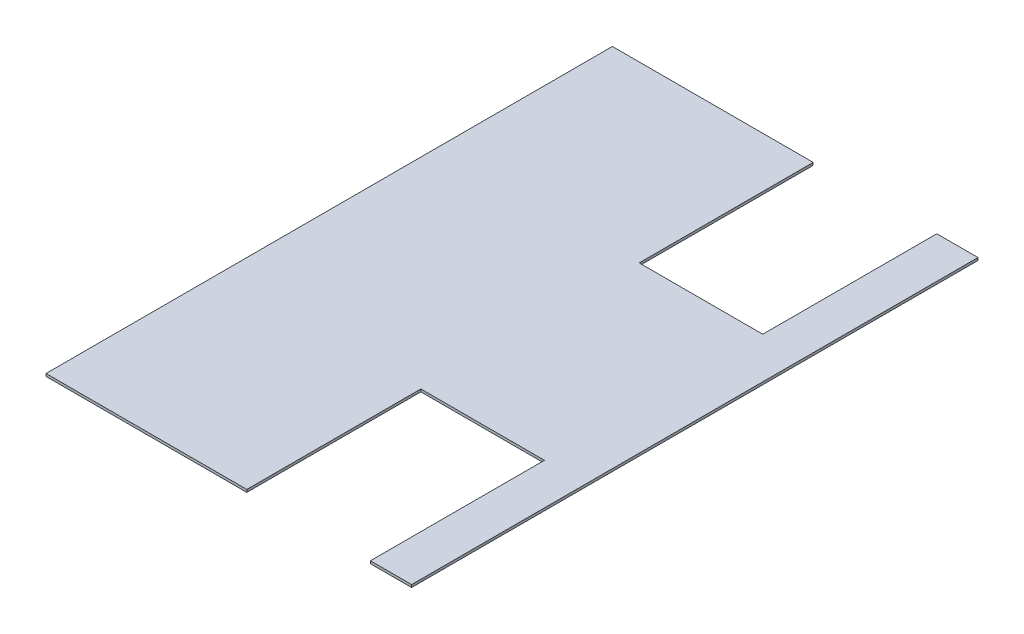
SolidWorks part; units mm, degrees
ref_plane "Front Plane" through (0, 0, 0) normal (0, 0, 1) x (1, 0, 0)
ref_plane "Top Plane" through (0, 0, 0) normal (0, 1, 0) x (1, 0, 0)
ref_plane "Right Plane" through (0, 0, 0) normal (1, 0, 0) x (0, 0, -1)
sketch "Sketch1" plane through (0, 0, 0) normal (0, 1, 0) x (1, 0, 0)
  line L0 (-11.8159, 446.3263) -> (38.9841, 446.3263)
  line L1 (-411.8659, 446.3263) -> (-164.2159, 446.3263)
  line L2 (-411.8659, 446.3263) -> (-411.8659, -252.1737)
  line L3 (-411.8659, -252.1737) -> (-164.2159, -252.1737)
  line L4 (38.9841, 446.3263) -> (38.9841, -252.1737)
  line L6 (-11.8159, -252.1737) -> (-11.8159, -37.5437)
  line L7 (-11.8159, -37.5437) -> (-164.2159, -37.5437)
  line L8 (-164.2159, -252.1737) -> (-164.2159, -37.5437)
  line L9 (-11.8159, -252.1737) -> (38.9841, -252.1737)
  line L10 (-11.8159, 446.3263) -> (-11.8159, 231.6963)
  line L11 (-11.8159, 231.6963) -> (-164.2159, 231.6963)
  line L12 (-164.2159, 446.3263) -> (-164.2159, 231.6963)
  dimension "D1" = 450.85
  dimension "D2" = 698.5
  dimension "D3" = 247.65
  dimension "D4" = 247.65
  dimension "D5" = 152.4
  dimension "D6" = 152.4
  dimension "D7" = 214.63
  dimension "D8" = 214.63
extrude "Boss-Extrude1" add sketch "Sketch1" along normal blind 3.175
